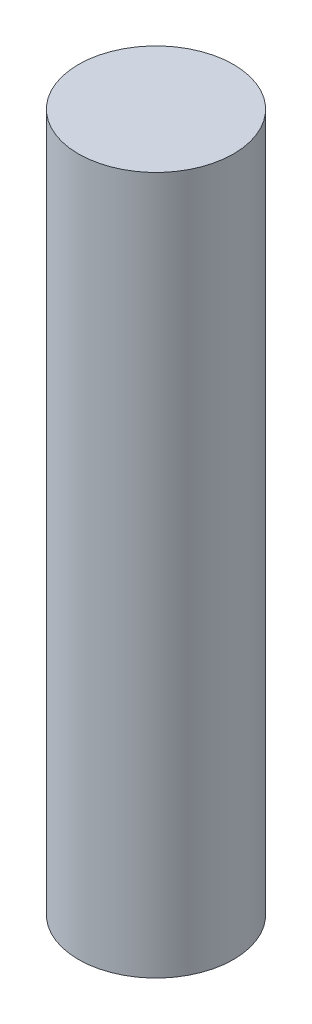
SolidWorks part; units mm, degrees
ref_plane "Спереди" through (0, 0, 0) normal (0, 0, 1) x (1, 0, 0)
ref_plane "Сверху" through (0, 0, 0) normal (0, 1, 0) x (1, 0, 0)
ref_plane "Справа" through (0, 0, 0) normal (1, 0, 0) x (0, 0, -1)
sketch "Эскиз2" plane through (0, 0, 0) normal (0, 1, 0) x (1, 0, 0)
  circle A0 centre (0, 0) radius 2
  dimension "D1" = 4
extrude "Бобышка-Вытянуть1" add sketch "Эскиз2" along normal blind 18
